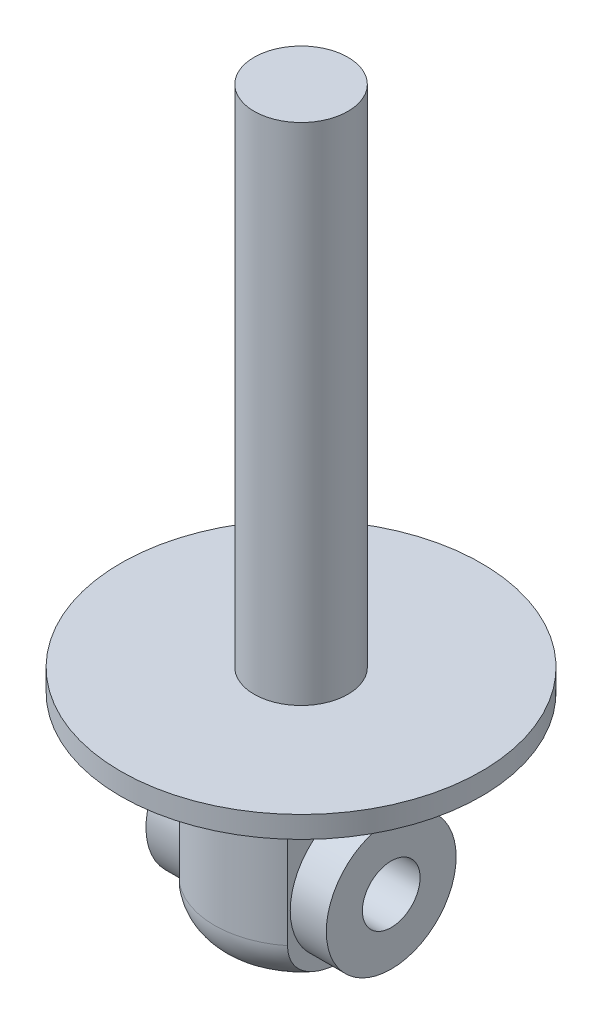
SolidWorks part; units mm, degrees
ref_plane "Front Plane" through (0, 0, 0) normal (0, 0, 1) x (1, 0, 0)
ref_plane "Top Plane" through (0, 0, 0) normal (0, 1, 0) x (1, 0, 0)
ref_plane "Right Plane" through (0, 0, 0) normal (1, 0, 0) x (0, 0, -1)
sketch "Sketch1" plane through (0, 0, 0) normal (0, 1, 0) x (1, 0, 0)
  circle A0 centre (0, 0) radius 25
  dimension "D1" = 50
extrude "Boss-Extrude1" add sketch "Sketch1" along normal blind 3
sketch "Sketch2" plane through (0, 3, 0) normal (0, 1, 0) x (1, 0, 0)
  circle A0 centre (0, 0) radius 6.5
  dimension "D1" = 13
extrude "Boss-Extrude2" add sketch "Sketch2" along normal blind 70
sketch "Sketch3" plane through (0, 0, 0) normal (0, -1, 0) x (1, 0, 0)
  circle A0 centre (0, 0) radius 12
  dimension "D1" = 24
extrude "Boss-Extrude3" add sketch "Sketch3" along normal blind 28
fillet "Fillet1" radius 6 1 edges at (0, -28, -12)
sketch "Sketch4" plane through (0, 0, 0) normal (0, 0, 1) x (1, 0, 0)
  line L0 (0, 0) -> (0, -28) construction
  line L1 (-6, -28) -> (6, -28) construction
  line L2 (-22.5, -28) -> (-22.5, -8)
  line L3 (7.5, -28) -> (22.5, -28)
  line L4 (7.5, -28) -> (7.5, -8)
  line L5 (7.5, -8) -> (22.5, -8)
  line L6 (22.5, -28) -> (22.5, -8)
  line L7 (-7.5, -8) -> (-22.5, -8)
  line L8 (-7.5, -28) -> (-7.5, -8)
  line L9 (-7.5, -28) -> (-22.5, -28)
  dimension "D1" = 7.5
  dimension "D2" = 20
  dimension "D3" = 15
extrude "Cut-Extrude1" cut sketch "Sketch4" against normal through all both and the other way through all
sketch "Sketch5" plane through (7.5, 0, 0) normal (1, 0, 0) x (0, 0, -1)
  line L0 (0, 0) -> (0, -28) construction
  line L1 (-6, -28) -> (6, -28) construction
  circle A0 centre (0, -18) radius 4
  dimension "D1" = 8
  dimension "D2" = 10
extrude "Cut-Extrude2" cut sketch "Sketch5" against normal through all both and the other way through all
sketch "Sketch7" plane through (0, 0, 0) normal (1, 0, 0) x (0, 0, -1)
  circle A0 centre (0, -18) radius 9
  circle A1 centre (0, -18) radius 4 construction
  circle A2 centre (0, -18) radius 4
  dimension "D1" = 18
extrude "Boss-Extrude4" add sketch "Sketch7" along normal mid plane 25 contours A0
sketch "Sketch8" plane through (0, 3, 0) normal (0, 1, 0) x (1, 0, 0)
  point P0 (0, 0)
